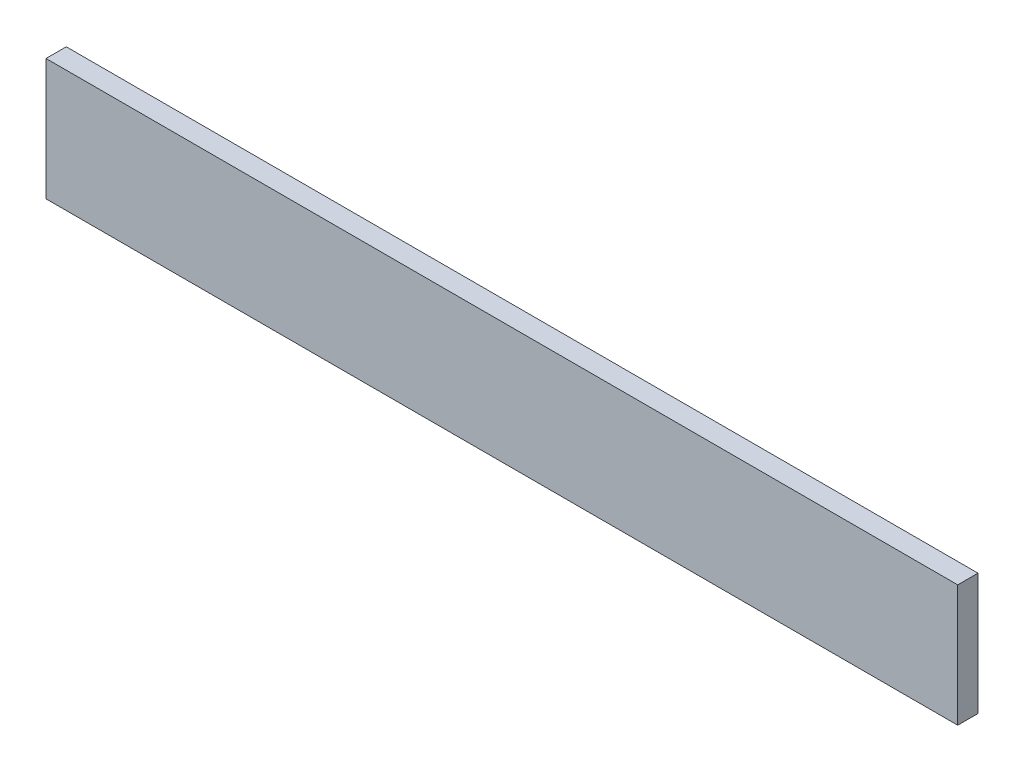
SolidWorks part; units mm, degrees
ref_plane "Plano frontal" through (0, 0, 0) normal (0, 0, 1) x (1, 0, 0)
ref_plane "Plano superior" through (0, 0, 0) normal (0, 1, 0) x (1, 0, 0)
ref_plane "Plano direito" through (0, 0, 0) normal (1, 0, 0) x (0, 0, -1)
sketch "Esboço1" plane through (0, 0, 0) normal (0, 0, 1) x (1, 0, 0)
  line L0 (0, 0) -> (0, 36)
  line L1 (0, 36) -> (-270, 36)
  line L2 (-270, 36) -> (-270, 0)
  line L3 (-270, 0) -> (0, 0)
  dimension "D1" = 36
  dimension "D2" = 270
extrude "Ressalto-extrusão1" add sketch "Esboço1" along normal blind 6
